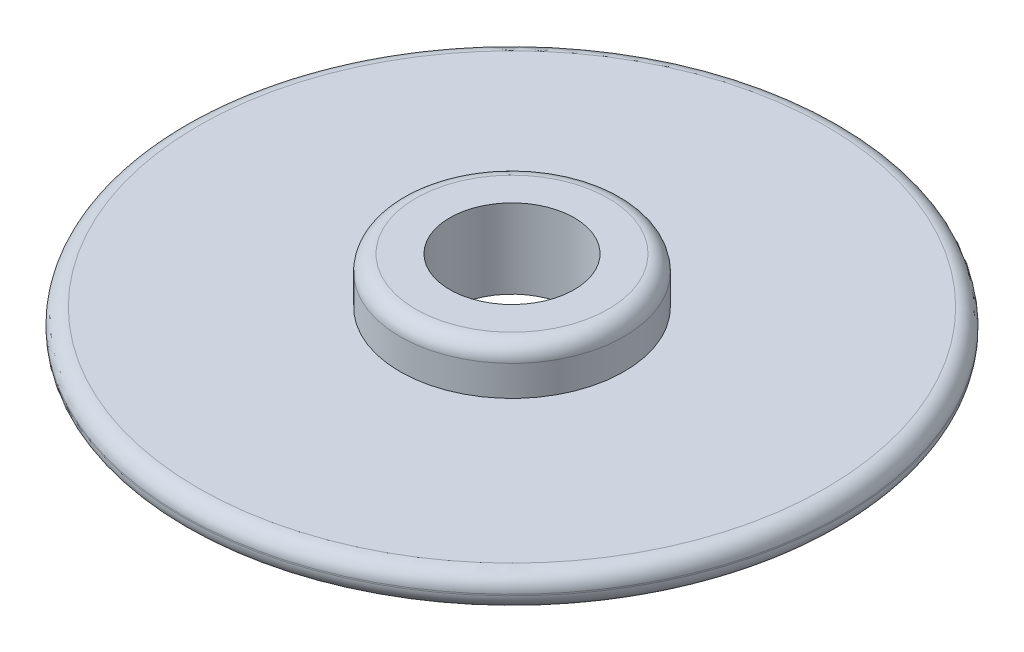
SolidWorks part; units mm, degrees
ref_plane "Front Plane" through (0, 0, 0) normal (0, 0, 1) x (1, 0, 0)
ref_plane "Top Plane" through (0, 0, 0) normal (0, 1, 0) x (1, 0, 0)
ref_plane "Right Plane" through (0, 0, 0) normal (1, 0, 0) x (0, 0, -1)
sketch "Sketch1" plane through (0, 0, 0) normal (0, 1, 0) x (1, 0, 0)
  circle A0 centre (0, 0) radius 15.875
  circle A1 centre (0, 0) radius 3
  dimension "D1" = 31.75
  dimension "D2" = 6
extrude "Boss-Extrude1" add sketch "Sketch1" along normal blind 3.81
sketch "Sketch2" plane through (0, 3.81, 0) normal (0, 1, 0) x (1, 0, 0)
  circle A0 centre (0, 0) radius 5.3975
  circle A1 centre (0, 0) radius 15.875
  circle A2 centre (0, 0) radius 15.875 construction
  dimension "D1" = 10.4775
extrude "Cut-Extrude1" cut sketch "Sketch2" against normal offset from surface (2.2225 mm away) 1.5875 up to face at (0, 0, 15.875)
fillet "Fillet1" radius 0.762 3 edges at (0, 0, 15.875) (0, 3.81, 5.3975) (0, 1.5875, 15.875)
